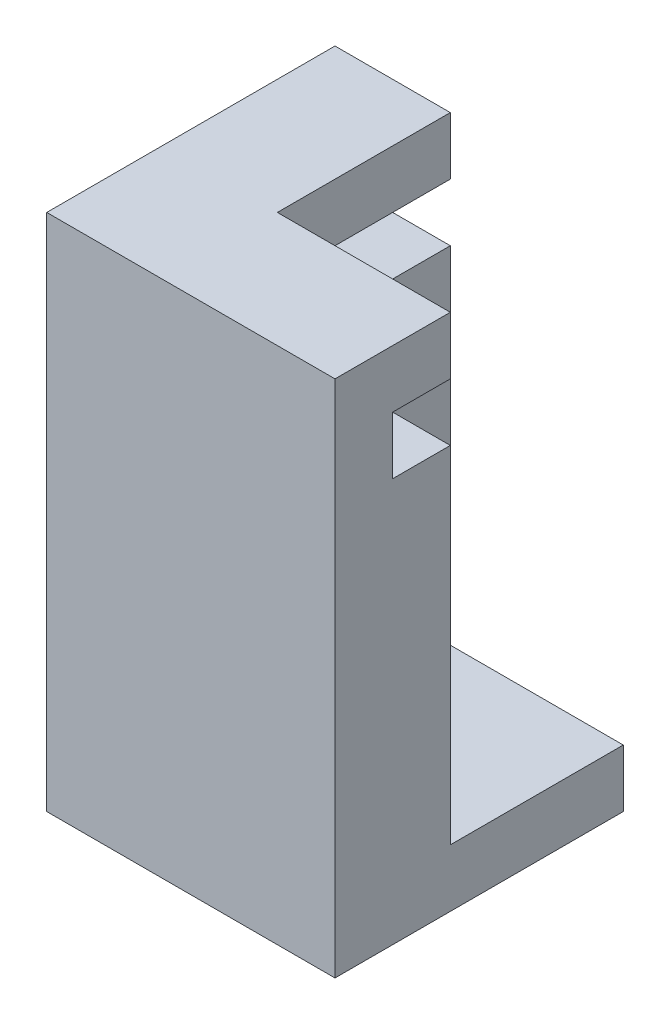
SolidWorks part; units mm, degrees
ref_plane "정면" through (0, 0, 0) normal (0, 0, 1) x (1, 0, 0)
ref_plane "윗면" through (0, 0, 0) normal (0, 1, 0) x (1, 0, 0)
ref_plane "우측면" through (0, 0, 0) normal (1, 0, 0) x (0, 0, -1)
sketch "스케치1" plane through (0, 0, 0) normal (0, 1, 0) x (1, 0, 0)
  line L0 (0, 0) -> (25, 0)
  line L17 (25, 0) -> (25, 10)
  line L18 (25, 10) -> (10, 10)
  line L19 (10, 10) -> (10, 25)
  line L20 (10, 25) -> (0, 25)
  line L21 (0, 25) -> (0, 0)
  dimension "D1" = 10
  dimension "D2" = 10
  dimension "D3" = 25
  dimension "D4" = 25
extrude "보스-돌출1" add sketch "스케치1" along normal blind 40
sketch "스케치2" plane through (0, 0, 0) normal (0, -1, 0) x (1, 0, 0)
  line L0 (25, 0) -> (25, -10) construction
  line L1 (0, 0) -> (25, 0)
  line L2 (0, 0) -> (0, -25)
  line L3 (0, -25) -> (25, -25)
  line L4 (25, 0) -> (25, -25)
  line L5 (10, -25) -> (0, -25) construction
extrude "보스-돌출2" add sketch "스케치2" along normal blind 5
sketch "스케치3" plane through (0, 0, -25) normal (0, 0, -1) x (-1, 0, 0)
  line L0 (-25, 40) -> (-25, 0) construction
  line L1 (-5, 30) -> (-25, 30)
  line L2 (-5, 30) -> (-5, 35)
  line L3 (-5, 35) -> (-25, 35)
  line L4 (-25, 30) -> (-25, 35)
  line L5 (-10, 40) -> (-10, 0) construction
  line L6 (-25, 40) -> (-10, 40) construction
  dimension "D1" = 5
  dimension "D2" = 5
  dimension "D3" = 5
extrude "컷-돌출1" cut sketch "스케치3" against normal blind 20
